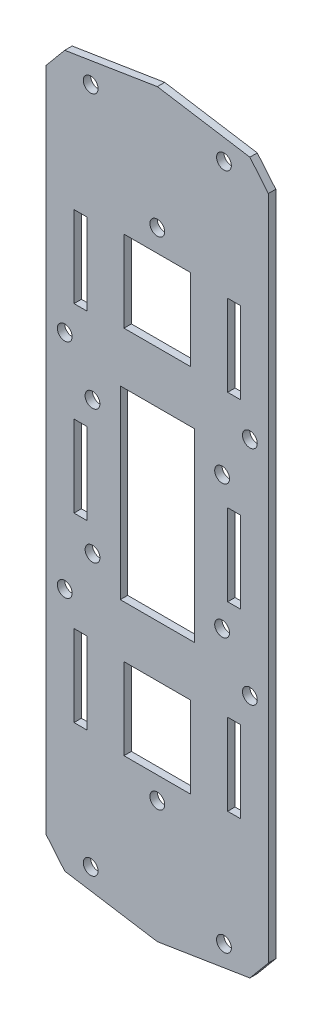
SolidWorks part; units mm, degrees
ref_plane "Front Plane" through (0, 0, 0) normal (0, 0, 1) x (1, 0, 0)
ref_plane "Top Plane" through (0, 0, 0) normal (0, 1, 0) x (1, 0, 0)
ref_plane "Right Plane" through (0, 0, 0) normal (1, 0, 0) x (0, 0, -1)
sketch "Sketch1" plane through (0, 0, 0) normal (0, 0, 1) x (1, 0, 0)
  line L0 (169.4354, 243.2996) -> (852.102, 243.2996) construction
  line L1 (-40, -100) -> (40, -100) construction
  line L2 (-40, -100) -> (-40, 100) construction
  line L3 (-40, 100) -> (40, 100) construction
  line L4 (40, -100) -> (40, 100) construction
  line L5 (-40, -100) -> (40, 100) construction
  line L6 (-40, 100) -> (40, -100) construction
  line L7 (-161.7244, -138.6454) -> (118.2756, -138.6454) construction
  line L8 (-161.7244, -138.6454) -> (-161.7244, 141.3546) construction
  line L9 (137.5032, 467.414) -> (1190.8365, 467.414) construction
  line L10 (0, -100) -> (0, 100) construction
  line L11 (0, -100) -> (-25, -96)
  line L12 (-25, -96) -> (-30, -90)
  line L13 (-30, -90) -> (-30, 90)
  line L14 (30, -90) -> (30, 90)
  line L16 (-10, -25) -> (10, -25)
  line L17 (-10, -25) -> (-10, 25)
  line L18 (-10, 25) -> (10, 25)
  line L19 (10, -25) -> (10, 25)
  line L20 (-10, -25) -> (10, 25) construction
  line L21 (-22.5, -38) -> (-19, -38)
  line L22 (19, 0) -> (-19, 0) construction
  line L23 (9, -61) -> (-9, -61)
  line L24 (9, -61) -> (9, -39)
  line L25 (9, -39) -> (-9, -39)
  line L26 (-9, -61) -> (-9, -39)
  line L27 (9, -61) -> (-9, -39) construction
  line L28 (9, -39) -> (-9, -61) construction
  line L29 (-22.5, -38) -> (-22.5, -60)
  line L30 (-19, -38) -> (-19, -60)
  line L31 (-22.5, -60) -> (-19, -60)
  line L32 (-22.5, 0) -> (-40, 0) construction
  line L33 (-19, -11) -> (-22.5, -11)
  line L34 (-19, -11) -> (-19, 11)
  line L35 (-22.5, 0) -> (-19, 0) construction
  line L36 (-22.5, -11) -> (-22.5, 11)
  line L37 (22.5, 0) -> (19, 0) construction
  line L38 (22.5, 0) -> (40, 0) construction
  line L39 (-10, 25) -> (10, -25) construction
  line L43 (22.5, -11) -> (22.5, 11)
  line L44 (19, -11) -> (19, 11)
  line L45 (19, -11) -> (22.5, -11)
  line L46 (22.5, -60) -> (19, -60)
  line L47 (19, -38) -> (19, -60)
  line L48 (22.5, -38) -> (22.5, -60)
  line L49 (9, -61) -> (9, -39)
  line L50 (22.5, -38) -> (19, -38)
  line L55 (25, -96) -> (30, -90)
  line L56 (0, -100) -> (25, -96)
  line L61 (9, 39) -> (-9, 61) construction
  line L62 (9, 61) -> (-9, 39) construction
  line L67 (-40, -100) -> (40, 100) construction
  line L68 (-40, 100) -> (40, -100) construction
  line L69 (-40, 100) -> (40, 100) construction
  line L70 (0, 100) -> (25, 96)
  line L71 (25, 96) -> (30, 90)
  line L75 (22.5, 38) -> (19, 38)
  line L76 (9, 61) -> (9, 39)
  line L77 (22.5, 38) -> (22.5, 60)
  line L78 (19, 38) -> (19, 60)
  line L79 (22.5, 60) -> (19, 60)
  line L80 (19, 11) -> (22.5, 11)
  line L81 (-19, 11) -> (-22.5, 11)
  line L82 (-22.5, 60) -> (-19, 60)
  line L83 (-19, 38) -> (-19, 60)
  line L84 (-22.5, 38) -> (-22.5, 60)
  line L85 (-9, 61) -> (-9, 39)
  line L86 (9, 39) -> (-9, 39)
  line L87 (9, 61) -> (9, 39)
  line L88 (9, 61) -> (-9, 61)
  line L89 (-22.5, 38) -> (-19, 38)
  line L93 (-25, 96) -> (-30, 90)
  line L94 (0, 100) -> (-25, 96)
  circle A0 centre (-18, -91.5) radius 2
  circle A5 centre (-25, -30) radius 2
  circle A6 centre (-17.5, -18) radius 2
  circle A7 centre (0, -67) radius 2
  circle A8 centre (17.5, -18) radius 2
  circle A9 centre (25, -30) radius 2
  circle A14 centre (18, -91.5) radius 2
  circle A15 centre (18, 91.5) radius 2
  circle A20 centre (25, 30) radius 2
  circle A21 centre (17.5, 18) radius 2
  circle A22 centre (0, 67) radius 2
  circle A23 centre (-17.5, 18) radius 2
  circle A24 centre (-25, 30) radius 2
  circle A29 centre (-18, 91.5) radius 2
  point P0 (0, 0)
  point P17 (0, 0)
  point P24 (0, -50)
  point P55 (0, 0)
  point P120 (25, 0)
  point P133 (-25, 0)
  point P137 (0, 50)
  dimension "D5" = 4
  dimension "D26" = 33
  dimension "D1" = 200
  dimension "D2" = 80
  dimension "D3" = 280
  dimension "D4" = 280
  dimension "D6" = 25
  dimension "D7" = 5
  dimension "D8" = 20
  dimension "D9" = 4
  dimension "D10" = 6
  dimension "D15" = 18
  dimension "D16" = 8.5
  dimension "D22" = 17.5
  dimension "D23" = 18
  dimension "D24" = 30
  dimension "D25" = 25
  dimension "D27" = 18
  dimension "D28" = 22
  dimension "D29" = 50
  dimension "D30" = 3.5
  dimension "D31" = 22
  dimension "D32" = 19
  dimension "D33" = 38
  dimension "D34" = 3.5
  dimension "D35" = 11
  dimension "D36" = 19
extrude "Boss-Extrude1" add sketch "Sketch1" along normal blind 2
